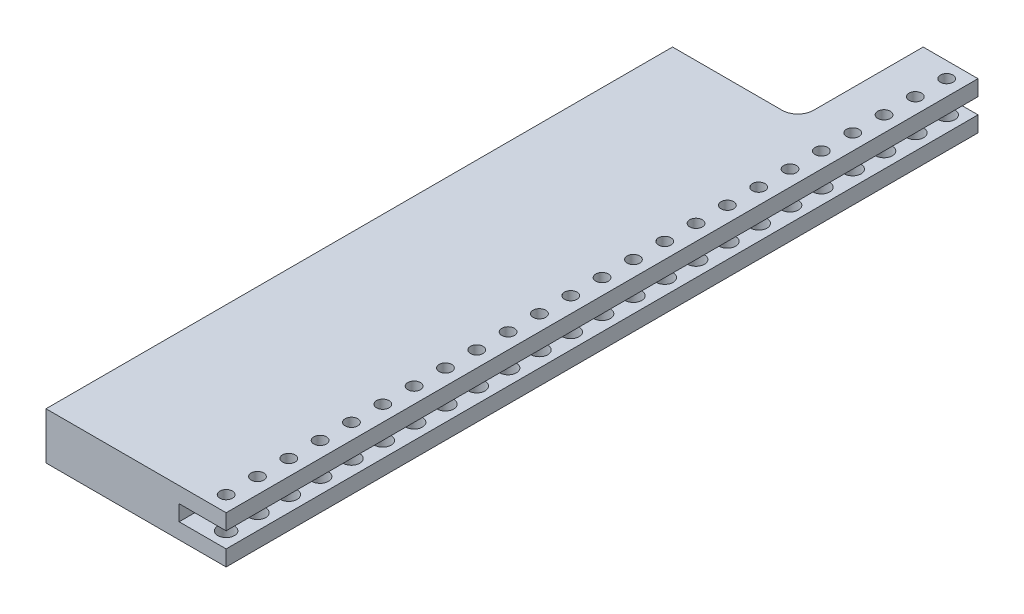
SolidWorks part; units mm, degrees
ref_plane "Front" through (0, 0, 0) normal (0, 0, 1) x (1, 0, 0)
ref_plane "Top" through (0, 0, 0) normal (0, 1, 0) x (1, 0, 0)
ref_plane "Right" through (0, 0, 0) normal (1, 0, 0) x (0, 0, -1)
sketch "Sketch1" plane through (0, 0, 0) normal (0, 1, 0) x (1, 0, 0)
  line L0 (-56.7627, -101.3183) -> (16.2623, -101.3183)
  line L1 (16.2623, -101.3183) -> (16.2623, 203.4817)
  line L2 (16.2623, 203.4817) -> (-5.9627, 203.4817)
  line L3 (-5.9627, 203.4817) -> (-5.9627, 152.6817)
  line L4 (-5.9627, 152.6817) -> (-56.7627, 152.6817)
  line L5 (-56.7627, 152.6817) -> (-56.7627, -101.3183)
  dimension "D1" = 304.8
  dimension "D2" = 254
  dimension "D3" = 50.8
  dimension "D4" = 73.025
extrude "Boss-Extrude1" add sketch "Sketch1" along normal mid plane 19.05 contours L4 L5 L0 L1 L2 L3
sketch "Sketch2" plane through (0, 0, 101.3183) normal (0, 0, 1) x (1, 0, 0)
  line L0 (50, 0) -> (-50, 0) construction
  line L1 (-2.7877, -3.175) -> (16.2623, -3.175)
  line L2 (-2.7877, -3.175) -> (-2.7877, 3.175)
  line L3 (-2.7877, 3.175) -> (16.2623, 3.175)
  line L4 (16.2623, -3.175) -> (16.2623, 3.175)
  line L5 (-2.7877, -3.175) -> (16.2623, 3.175) construction
  line L6 (-2.7877, 3.175) -> (16.2623, -3.175) construction
  line L7 (16.2623, 9.525) -> (16.2623, -9.525) construction
  point P0 (6.7373, 0)
  dimension "D1" = 6.35
  dimension "D2" = 19.05
extrude "Cut-Extrude1" cut sketch "Sketch2" against normal up to next
fillet "Fillet1" radius 6.35 1 edges at (-5.9627, 0, -152.6817)
sketch "Sketch3" plane through (0, 9.525, 0) normal (0, 1, 0) x (1, 0, 0)
  line L0 (16.2623, -101.3183) -> (16.2623, 203.4817) construction
  line L1 (16.2623, 203.4817) -> (-5.9627, 203.4817) construction
  point P0 (9.9123, 197.1317)
  dimension "D1" = 6.35
  dimension "D2" = 6.35
hole_wizard "1/4 (0.25) Diameter Hole1" [suppressed] positions "Sketch4" profile "Sketch6" hole size "1/4" standard "ANSI Inch"
sketch "Sketch4" plane through (0, 9.525, 0) normal (0, 1, 0) x (1, 0, 0)
  point P0 (9.9123, 197.1317)
sketch "Sketch6" plane through (9.9123, 9.525, -197.1317) normal (1, 0, 0) x (0, 0, 1)
  line L0 (0, 0) -> (0, 6.35)
  line L1 (0, 6.35) -> (3.175, 6.35)
  line L2 (3.175, 6.35) -> (3.175, 0)
  line L5 (3.175, 0) -> (0, 0)
  line L11 (0, -6.35) -> (0, 107.95) construction
  dimension "Thru Hole Dia." = 6.35
  dimension "Thru Hole Depth" = 6.35
hole_wizard "1/4-20 Tapped Hole1" [suppressed] positions "Sketch7" profile "Sketch9" tap size "1/4-20" standard "ANSI Inch"
sketch "Sketch7" plane through (0, -3.175, 0) normal (0, 1, 0) x (1, 0, 0)
  point P0 (9.9123, 197.1317)
sketch "Sketch9" plane through (9.9123, -3.175, -197.1317) normal (1, 0, 0) x (0, 0, 1)
  line L0 (0, 0) -> (0, 6.35)
  line L1 (0, 6.35) -> (2.5527, 6.35)
  line L2 (2.5527, 6.35) -> (2.5527, 0)
  line L5 (2.5527, 0) -> (0, 0)
  line L11 (0, -6.35) -> (0, 107.95) construction
  dimension "Thru Tap Drill Dia." = 5.1054
  dimension "Thru Tap Drill Depth" = 6.35
cosmetic thread "Hole Thread1" [suppressed] parameters "D2"=6.35
pattern_linear "LPattern1" [suppressed] count 24 spacing 12.7
cosmetic thread "Hole Thread2" [suppressed] parameters "D2"=6.35
cosmetic thread "Hole Thread3" [suppressed] parameters "D2"=6.35
cosmetic thread "Hole Thread4" [suppressed] parameters "D2"=6.35
cosmetic thread "Hole Thread5" [suppressed] parameters "D2"=6.35
cosmetic thread "Hole Thread6" [suppressed] parameters "D2"=6.35
cosmetic thread "Hole Thread7" [suppressed] parameters "D2"=6.35
cosmetic thread "Hole Thread8" [suppressed] parameters "D2"=6.35
cosmetic thread "Hole Thread9" [suppressed] parameters "D2"=6.35
cosmetic thread "Hole Thread10" [suppressed] parameters "D2"=6.35
cosmetic thread "Hole Thread11" [suppressed] parameters "D2"=6.35
cosmetic thread "Hole Thread12" [suppressed] parameters "D2"=6.35
cosmetic thread "Hole Thread13" [suppressed] parameters "D2"=6.35
cosmetic thread "Hole Thread14" [suppressed] parameters "D2"=6.35
cosmetic thread "Hole Thread15" [suppressed] parameters "D2"=6.35
cosmetic thread "Hole Thread16" [suppressed] parameters "D2"=6.35
cosmetic thread "Hole Thread17" [suppressed] parameters "D2"=6.35
cosmetic thread "Hole Thread18" [suppressed] parameters "D2"=6.35
cosmetic thread "Hole Thread19" [suppressed] parameters "D2"=6.35
cosmetic thread "Hole Thread20" [suppressed] parameters "D2"=6.35
cosmetic thread "Hole Thread21" [suppressed] parameters "D2"=6.35
cosmetic thread "Hole Thread22" [suppressed] parameters "D2"=6.35
cosmetic thread "Hole Thread23" [suppressed] parameters "D2"=6.35
cosmetic thread "Hole Thread24" [suppressed] parameters "D2"=6.35
hole_wizard "1/4-20 Tapped Hole2" positions "Sketch10" profile "Sketch11" tap size "1/4-20" standard "ANSI Inch"
sketch "Sketch10" plane through (0, 9.525, 0) normal (0, 1, 0) x (1, 0, 0)
  point P0 (9.9123, 197.1317)
sketch "Sketch11" plane through (9.9123, 9.525, -197.1317) normal (1, 0, 0) x (0, 0, 1)
  line L0 (0, 0) -> (0, 6.35)
  line L1 (0, 6.35) -> (2.5527, 6.35)
  line L2 (2.5527, 6.35) -> (2.5527, 0)
  line L5 (2.5527, 0) -> (0, 0)
  line L11 (0, -6.35) -> (0, 107.95) construction
  dimension "Thru Tap Drill Dia." = 5.1054
  dimension "Thru Tap Drill Depth" = 6.35
cosmetic thread "Hole Thread25" parameters "D2"=6.35
hole_wizard "1/4 Clearance Hole1" positions "Sketch12" profile "Sketch14" hole size "1/4" standard "ANSI Inch"
sketch "Sketch12" plane through (0, -3.175, 0) normal (0, 1, 0) x (1, 0, 0)
  point P0 (9.9123, 197.1317)
sketch "Sketch14" plane through (9.9123, -3.175, -197.1317) normal (1, 0, 0) x (0, 0, 1)
  line L0 (0, 0) -> (0, 6.35)
  line L1 (0, 6.35) -> (3.3782, 6.35)
  line L2 (3.3782, 6.35) -> (3.3782, 0)
  line L5 (3.3782, 0) -> (0, 0)
  line L11 (0, -6.35) -> (0, 107.95) construction
  dimension "Thru Hole Dia." = 6.7564
  dimension "Thru Hole Depth" = 6.35
pattern_linear "LPattern2" count 24 spacing 12.7 along (0, 0, 1) of "1/4 Clearance Hole1", "1/4-20 Tapped Hole2"
cosmetic thread "Hole Thread26" parameters "D2"=6.35
cosmetic thread "Hole Thread27" parameters "D2"=6.35
cosmetic thread "Hole Thread28" parameters "D2"=6.35
cosmetic thread "Hole Thread29" parameters "D2"=6.35
cosmetic thread "Hole Thread30" parameters "D2"=6.35
cosmetic thread "Hole Thread31" parameters "D2"=6.35
cosmetic thread "Hole Thread32" parameters "D2"=6.35
cosmetic thread "Hole Thread33" parameters "D2"=6.35
cosmetic thread "Hole Thread34" parameters "D2"=6.35
cosmetic thread "Hole Thread35" parameters "D2"=6.35
cosmetic thread "Hole Thread36" parameters "D2"=6.35
cosmetic thread "Hole Thread37" parameters "D2"=6.35
cosmetic thread "Hole Thread38" parameters "D2"=6.35
cosmetic thread "Hole Thread39" parameters "D2"=6.35
cosmetic thread "Hole Thread40" parameters "D2"=6.35
cosmetic thread "Hole Thread41" parameters "D2"=6.35
cosmetic thread "Hole Thread42" parameters "D2"=6.35
cosmetic thread "Hole Thread43" parameters "D2"=6.35
cosmetic thread "Hole Thread44" parameters "D2"=6.35
cosmetic thread "Hole Thread45" parameters "D2"=6.35
cosmetic thread "Hole Thread46" parameters "D2"=6.35
cosmetic thread "Hole Thread47" parameters "D2"=6.35
cosmetic thread "Hole Thread48" parameters "D2"=6.35
